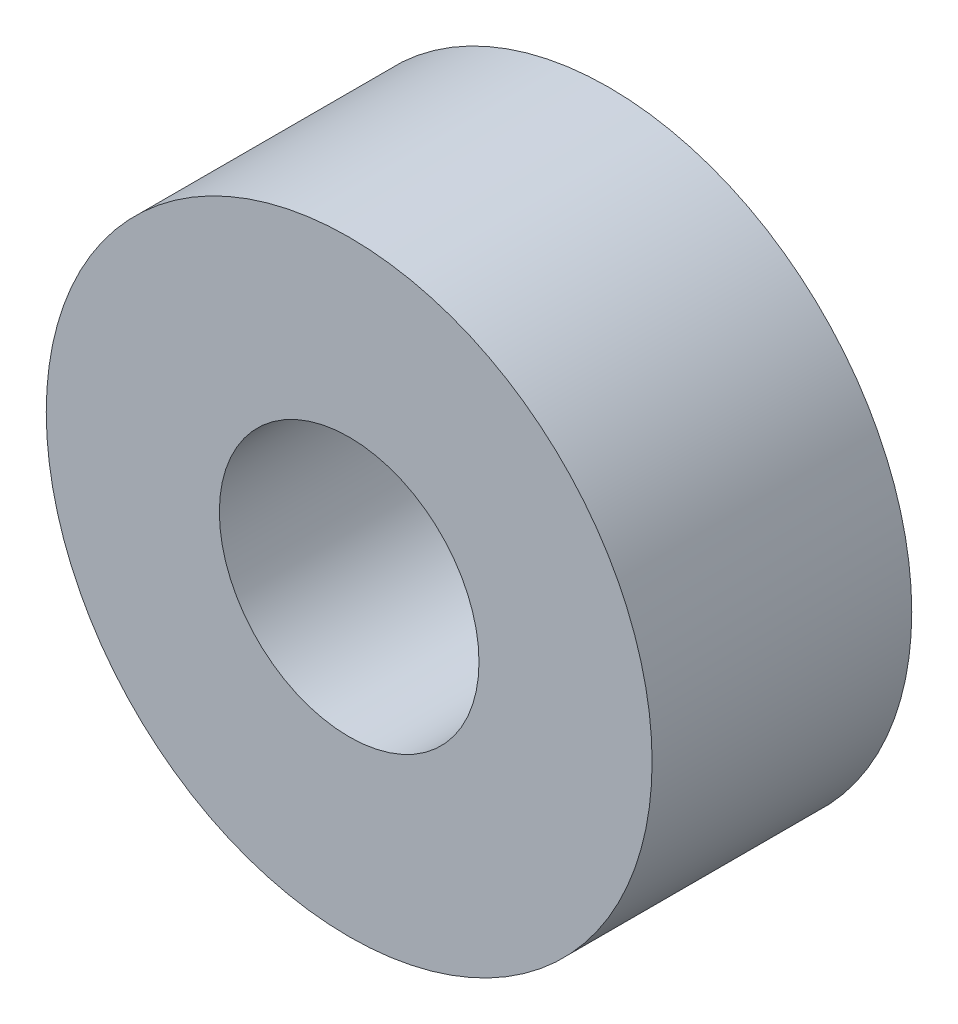
SolidWorks part; units mm, degrees
ref_plane "Front Plane" through (0, 0, 0) normal (0, 0, 1) x (1, 0, 0)
ref_plane "Top Plane" through (0, 0, 0) normal (0, 1, 0) x (1, 0, 0)
ref_plane "Right Plane" through (0, 0, 0) normal (1, 0, 0) x (0, 0, -1)
sketch "Sketch1" plane through (0, 0, 0) normal (0, 0, 1) x (1, 0, 0)
  circle A0 centre (0, 0) radius 4.7625
  circle A1 centre (0, 0) radius 11.1125
  dimension "D1" = 9.525
  dimension "D2" = 22.225
extrude "Boss-Extrude1" add sketch "Sketch1" along normal blind 9.525
